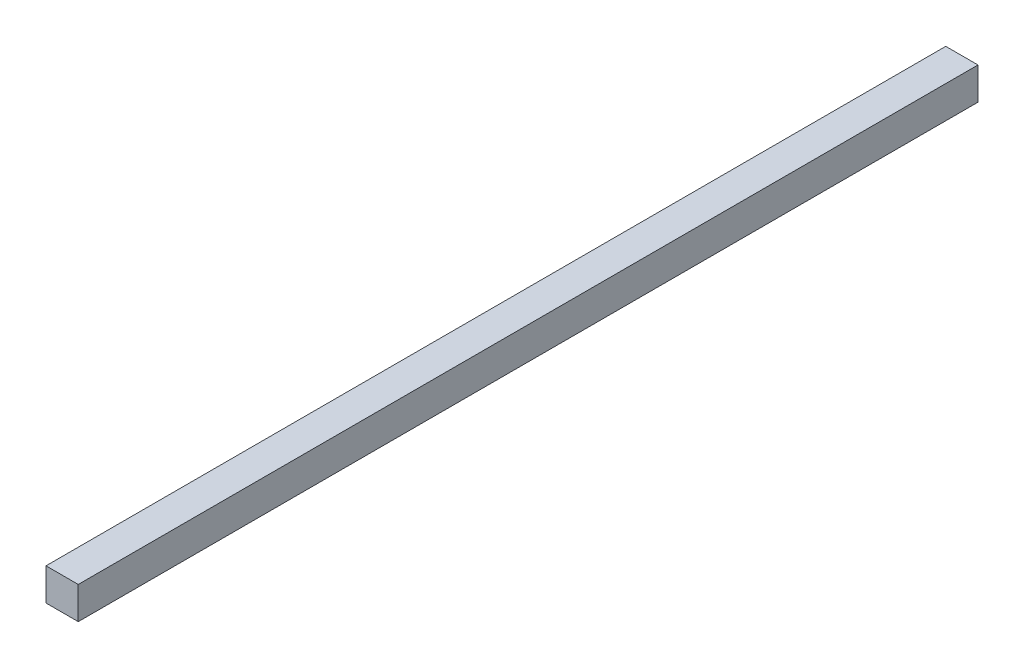
SolidWorks part; units mm, degrees
ref_plane "Front Plane" through (0, 0, 0) normal (0, 0, 1) x (1, 0, 0)
ref_plane "Top Plane" through (0, 0, 0) normal (0, 1, 0) x (1, 0, 0)
ref_plane "Right Plane" through (0, 0, 0) normal (1, 0, 0) x (0, 0, -1)
sketch "Sketch1" plane through (0, 0, 0) normal (0, 0, 1) x (1, 0, 0)
  line L1 (-1, 1) -> (1, 1)
  line L2 (-1, 1) -> (-1, -1)
  line L3 (-1, -1) -> (1, -1)
  line L4 (1, 1) -> (1, -1)
  line L5 (-1, 1) -> (1, -1) construction
  line L6 (-1, -1) -> (1, 1) construction
  point P0 (0, 0)
  dimension "D1" = 2
  dimension "D2" = 2
extrude "Boss-Extrude1" add sketch "Sketch1" along normal blind 55.8
